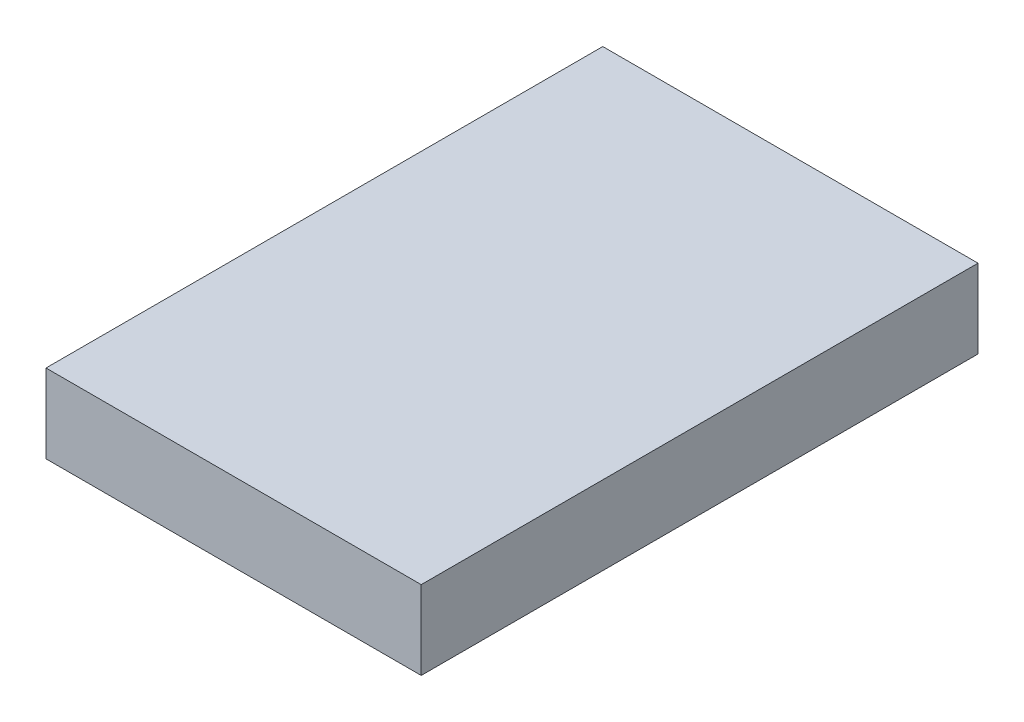
SolidWorks part; units mm, degrees
ref_plane "Front Plane" through (0, 0, 0) normal (0, 0, 1) x (1, 0, 0)
ref_plane "Top Plane" through (0, 0, 0) normal (0, 1, 0) x (1, 0, 0)
ref_plane "Right Plane" through (0, 0, 0) normal (1, 0, 0) x (0, 0, -1)
sketch "Sketch1" plane through (0, 0, 0) normal (0, 1, 0) x (1, 0, 0)
  line L1 (-39.37, -58.42) -> (39.37, -58.42)
  line L2 (-39.37, -58.42) -> (-39.37, 58.42)
  line L3 (-39.37, 58.42) -> (39.37, 58.42)
  line L4 (39.37, -58.42) -> (39.37, 58.42)
  line L5 (-39.37, -58.42) -> (39.37, 58.42) construction
  line L6 (-39.37, 58.42) -> (39.37, -58.42) construction
  point P0 (0, 0)
  dimension "D1" = 78.74
  dimension "D2" = 116.84
extrude "Boss-Extrude1" add sketch "Sketch1" along normal blind 16.51
